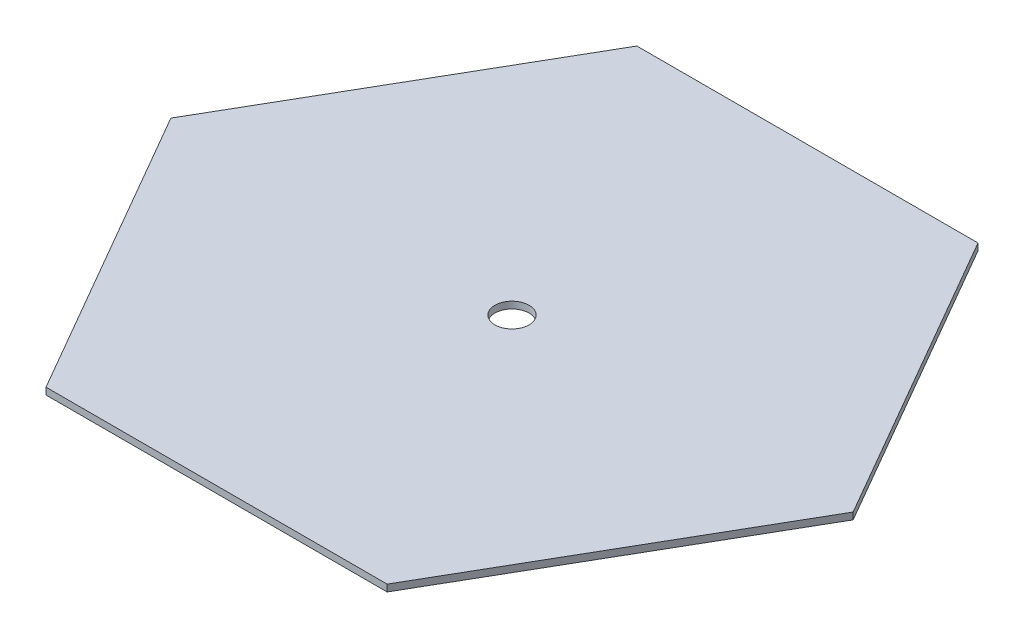
SolidWorks part; units mm, degrees
material "Ti-6Al-4VSolution treated and aged (SS)"
ref_plane "Front Plane" through (0, 0, 0) normal (0, 0, 1) x (1, 0, 0)
ref_plane "Top Plane" through (0, 0, 0) normal (0, 1, 0) x (1, 0, 0)
ref_plane "Right Plane" through (0, 0, 0) normal (1, 0, 0) x (0, 0, -1)
sketch "Sketch1" plane through (0, 0, 0) normal (0, 1, 0) x (1, 0, 0)
  line L1 (500, 0) -> (250, 433.0127)
  line L2 (250, 433.0127) -> (-250, 433.0127)
  line L3 (-250, 433.0127) -> (-500, 0)
  line L4 (-500, 0) -> (-250, -433.0127)
  line L5 (-250, -433.0127) -> (250, -433.0127)
  line L6 (250, -433.0127) -> (500, 0)
  circle A0 centre (0, 0) radius 433.0127 construction
  dimension "D1" = 500
extrude "Boss-Extrude1" add sketch "Sketch1" along normal blind 10
sketch "Sketch4" plane through (0, 0, 0) normal (0, -1, 0) x (1, 0, 0)
  circle A0 centre (0, 0) radius 25
  dimension "D1" = 50
extrude "Cut-Extrude2" cut sketch "Sketch4" against normal through all
